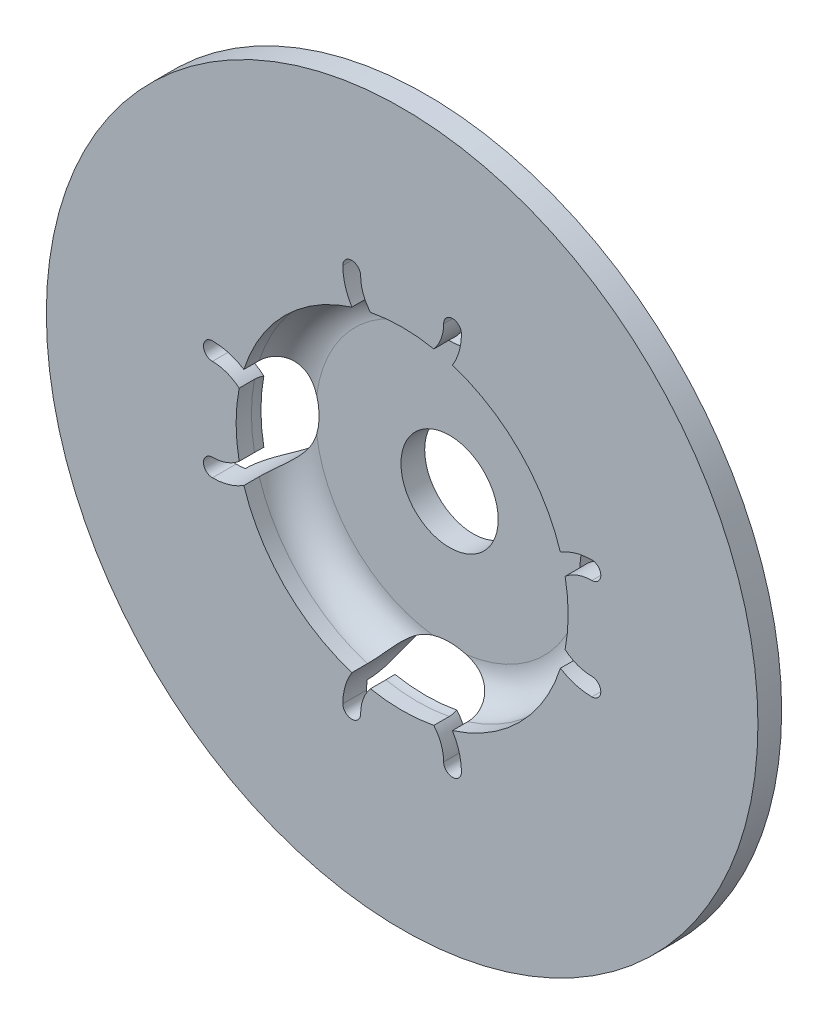
SolidWorks part; units mm, degrees
ref_plane "Front Plane" through (0, 0, 0) normal (0, 0, 1) x (1, 0, 0)
ref_plane "Top Plane" through (0, 0, 0) normal (0, 1, 0) x (1, 0, 0)
ref_plane "Right Plane" through (0, 0, 0) normal (1, 0, 0) x (0, 0, -1)
sketch "Sketch1" plane through (0, 0, 0) normal (0, 1, 0) x (1, 0, 0)
  line L0 (0, 0) -> (0, 1)
  line L1 (0, 1) -> (7, 1)
  line L2 (9, 3) -> (15, 3)
  line L3 (15, 3) -> (15, 0) construction
  line L4 (15, 0) -> (0, 0) construction
  line L5 (15, 3) -> (15, 2)
  line L6 (15, 2) -> (9.3536, 2)
  line L7 (8, 0) -> (0, 0)
  line L8 (8, 0) -> (8, 0.6464)
  arc A0 (7, 1) -> (9, 3) centre (9, 1) cw
  arc A1 (9.3536, 2) -> (8, 0.6464) centre (9.3536, 0.6464) ccw
  point P11 (8.1134, 0.7077)
  dimension "D4" = 15
  dimension "D6" = 0.5
  dimension "D1" = 1
  dimension "D2" = 8
  dimension "D3" = 2
  dimension "D5" = 1
  dimension "D7" = 1
revolve "Revolve1" add sketch "Sketch1" angle 360 about L3
sketch "Sketch2" plane through (0, 0, -3) normal (0, 0, -1) x (-1, 0, 0)
  line L0 (-15, 0) -> (-15, 6) construction
  line L1 (-17.5, 8) -> (-12.5, 8) construction
  circle A0 centre (-15, 0) radius 6 construction
  circle A1 centre (-15, 8) radius 2.5
  circle A2 centre (-15, 0) radius 8 construction
  circle A3 centre (-7, 0) radius 2.5
  circle A4 centre (-15, -8) radius 2.5
  circle A5 centre (-23, 0) radius 2.5
  point P11 (7.4354, 12.1856)
  point P12 (0, 0)
  point P20 (-15, 0)
  dimension "D1" = 5
  dimension "D2" = 4
extrude "Cut-Extrude1" cut sketch "Sketch2" against normal up to surface (2 mm away) up to face at (0, 0, -1)
sketch "Sketch3" plane through (0, 0, -1) normal (0, 0, -1) x (-1, 0, 0)
  line L0 (-15, -8) -> (-16.75, -8) construction
  line L1 (-16.75, -8) -> (-17.5, -8) construction
  line L2 (-15, -8) -> (-15, -9.75) construction
  circle A0 centre (-15, -8) radius 2.5 construction
  arc A1 (-12.5, -8) -> (-17.5, -8) centre (-15, -8) ccw
  arc A2 (-13.25, -8) -> (-16.75, -8) centre (-15, -8) ccw
  arc A3 (-17.5, -8) -> (-16.75, -8) centre (-17.125, -8) ccw
  arc A4 (-12.5, -8) -> (-13.25, -8) centre (-12.875, -8) cw
  arc A5 (-23, -1.75) -> (-23, 1.75) centre (-23, 0) ccw
  arc A6 (-23, 2.5) -> (-23, 1.75) centre (-23, 2.125) ccw
  arc A7 (-23, -2.5) -> (-23, 2.5) centre (-23, 0) ccw
  arc A8 (-23, -2.5) -> (-23, -1.75) centre (-23, -2.125) cw
  arc A9 (-16.75, 8) -> (-13.25, 8) centre (-15, 8) ccw
  arc A10 (-12.5, 8) -> (-13.25, 8) centre (-12.875, 8) ccw
  arc A11 (-17.5, 8) -> (-12.5, 8) centre (-15, 8) ccw
  arc A12 (-17.5, 8) -> (-16.75, 8) centre (-17.125, 8) cw
  arc A13 (-7, 1.75) -> (-7, -1.75) centre (-7, 0) ccw
  arc A14 (-7, -2.5) -> (-7, -1.75) centre (-7, -2.125) ccw
  arc A15 (-7, 2.5) -> (-7, -2.5) centre (-7, 0) ccw
  arc A16 (-7, 2.5) -> (-7, 1.75) centre (-7, 2.125) cw
  point P9 (-17.125, -8)
  point P34 (-15, 0)
  point P35 (-15, 0)
  dimension "D1" = 3.5
  dimension "D2" = 4
extrude "Cut-Extrude2" cut sketch "Sketch3" against normal blind 10
sketch "Sketch4" plane through (0, 0, -3) normal (0, 0, -1) x (-1, 0, 0)
  circle A0 centre (-15, 0) radius 2.05
  dimension "D1" = 4.1
extrude "Cut-Extrude3" cut sketch "Sketch4" against normal blind 10
